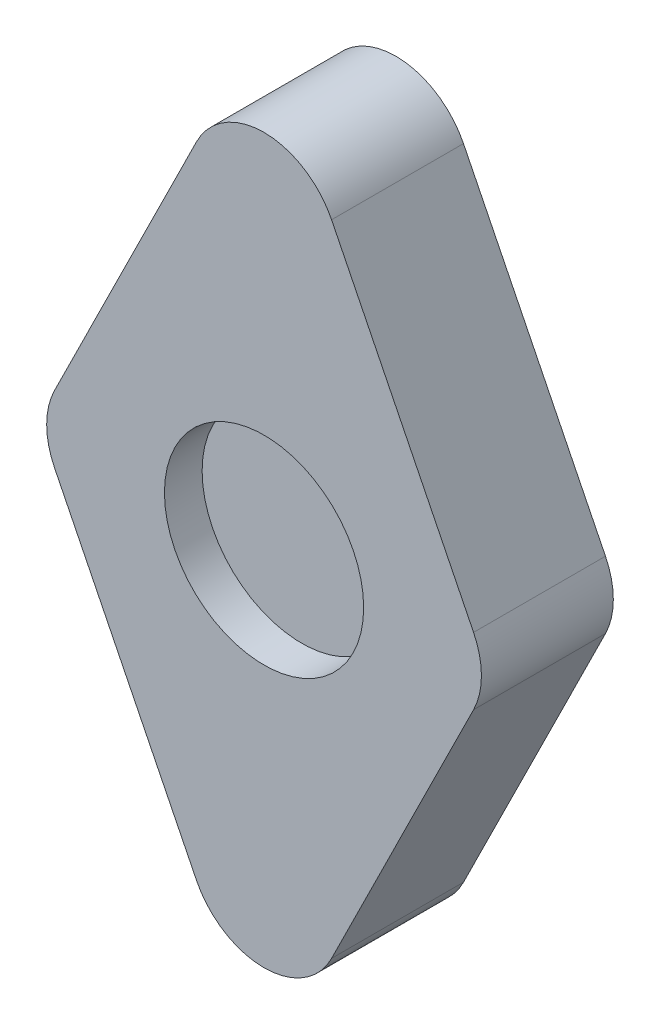
SolidWorks part; units mm, degrees
ref_plane "Front Plane" through (0, 0, 0) normal (0, 0, 1) x (1, 0, 0)
ref_plane "Top Plane" through (0, 0, 0) normal (0, 1, 0) x (1, 0, 0)
ref_plane "Right Plane" through (0, 0, 0) normal (1, 0, 0) x (0, 0, -1)
sketch "Sketch1" plane through (0, 0, 0) normal (0, 0, 1) x (1, 0, 0)
  line L0 (-28.2419, 4.5136) -> (-9.1024, 43.1115)
  line L1 (-28.2419, -4.5136) -> (-9.1024, -43.1115)
  line L2 (9.1024, 43.1115) -> (28.2419, 4.5136)
  line L3 (28.2419, -4.5136) -> (9.1024, -43.1115)
  arc A0 (-9.1024, -43.1115) -> (9.1024, -43.1115) centre (0, -38.598) ccw
  arc A1 (28.2419, 4.5136) -> (28.2419, -4.5136) centre (19.1395, 0) cw
  arc A2 (-9.1024, 43.1115) -> (9.1024, 43.1115) centre (0, 38.598) cw
  arc A3 (-28.2419, 4.5136) -> (-28.2419, -4.5136) centre (-19.1395, 0) ccw
  point P6 (0, -61.468)
  point P10 (30.48, 0)
  point P13 (0, 61.468)
  point P16 (-30.48, 0)
  dimension "D5" = 10.16
  dimension "D1" = 30.48
  dimension "D2" = 30.48
  dimension "D3" = 61.468
  dimension "D4" = 61.468
extrude "Boss-Extrude1" add sketch "Sketch1" along normal blind 17.78
sketch "Sketch2" plane through (0, 0, 17.78) normal (0, 0, 1) x (1, 0, 0)
  circle A0 centre (0, 0) radius 13.426
extrude "Cut-Extrude1" cut sketch "Sketch2" against normal blind 5.08
scale "Scale1" bodies to scale 102 scale about centroid uniform scaling yes scale factor 1.5
scale "Scale2" bodies to scale 103 scale about centroid uniform scaling yes scale factor 2
sketch "Sketch3" plane through (0, 0, -17.174) normal (0, 0, -1) x (-1, 0, 0)
  line L0 (0, 84.1429) -> (0, -83.2572) construction
  circle A0 centre (-44.45, 0) radius 25.4
  circle A1 centre (44.45, 0) radius 25.4
  dimension "D1" = 50.8
  dimension "D2" = 50.8
  dimension "D4" = 44.45
  dimension "D3" = 88.9
extrude "Cut-Extrude2" cut sketch "Sketch3" against normal blind 15.24
